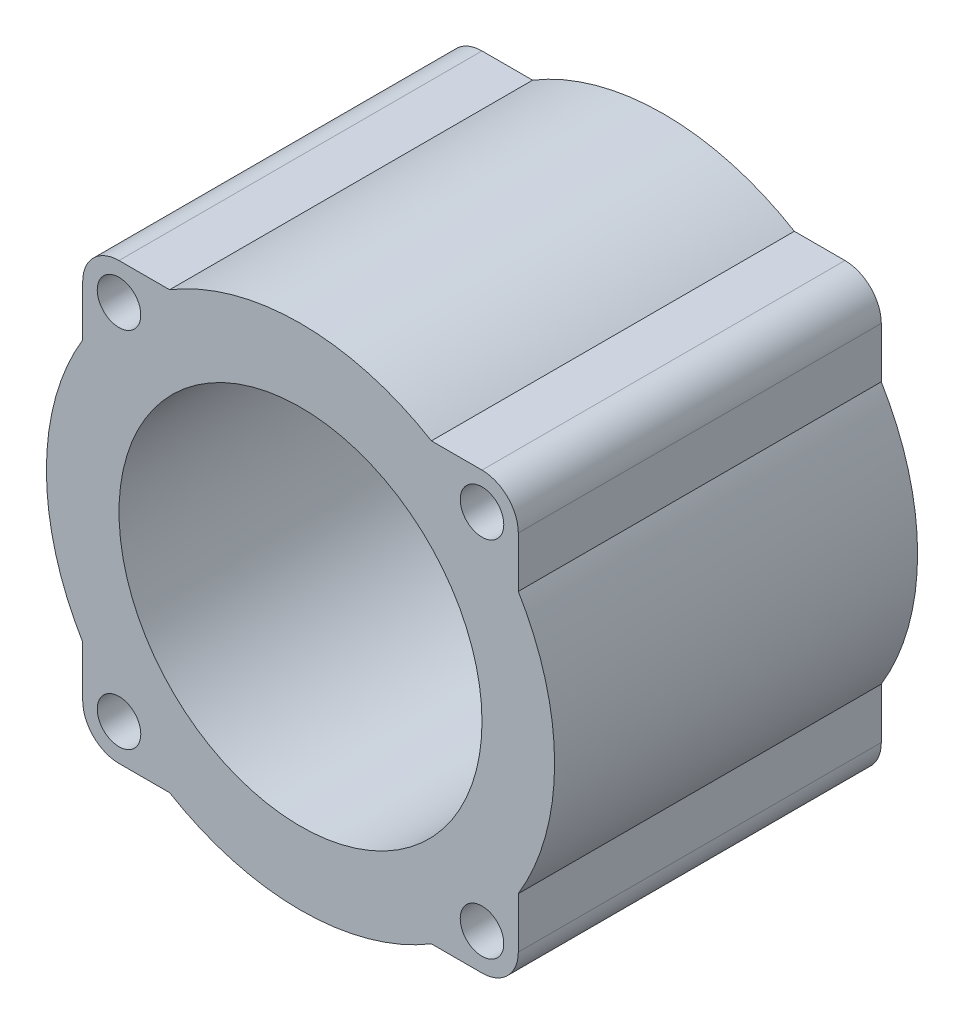
SolidWorks part; units mm, degrees
ref_plane "Front Plane" through (0, 0, 0) normal (0, 0, 1) x (1, 0, 0)
ref_plane "Top Plane" through (0, 0, 0) normal (0, 1, 0) x (1, 0, 0)
ref_plane "Right Plane" through (0, 0, 0) normal (1, 0, 0) x (0, 0, -1)
sketch "Sketch1" plane through (0, 0, 0) normal (0, 0, 1) x (1, 0, 0)
  line L0 (0, 9.1546) -> (0, -8.5913) construction
  line L5 (-9.5382, 0) -> (12.5098, 0) construction
  line L6 (3.6056, 6) -> (5, 6)
  line L7 (6, 5) -> (6, 3.6056)
  line L8 (-6, 5) -> (-6, 3.6056)
  line L9 (-3.6056, 6) -> (-5, 6)
  line L10 (6, -5) -> (6, -3.6056)
  line L11 (3.6056, -6) -> (5, -6)
  line L12 (-6, -5) -> (-6, -3.6056)
  line L13 (-3.6056, -6) -> (-5, -6)
  arc A16 (3.6056, 6) -> (-3.6056, 6) centre (0, 0) ccw
  arc A17 (6, 5) -> (5, 6) centre (5, 5) ccw
  circle A18 centre (5, 5) radius 0.6
  circle A19 centre (-5, 5) radius 0.6
  arc A20 (-6, 5) -> (-5, 6) centre (-5, 5) cw
  circle A21 centre (5, -5) radius 0.6
  arc A22 (6, -5) -> (5, -6) centre (5, -5) cw
  circle A23 centre (-5, -5) radius 0.6
  arc A24 (-6, -5) -> (-5, -6) centre (-5, -5) ccw
  arc A25 (-6, 3.6056) -> (-6, -3.6056) centre (0, 0) ccw
  arc A26 (-3.6056, -6) -> (3.6056, -6) centre (0, 0) ccw
  arc A27 (6, -3.6056) -> (6, 3.6056) centre (0, 0) ccw
  circle A28 centre (0, 0) radius 5
  dimension "D2" = 6
  dimension "D1" = 14
  dimension "D4" = 1
  dimension "D5" = 1.2
  dimension "D6" = 10
  dimension "D3" = 6
extrude "Boss-Extrude1" add sketch "Sketch1" along normal blind 10
